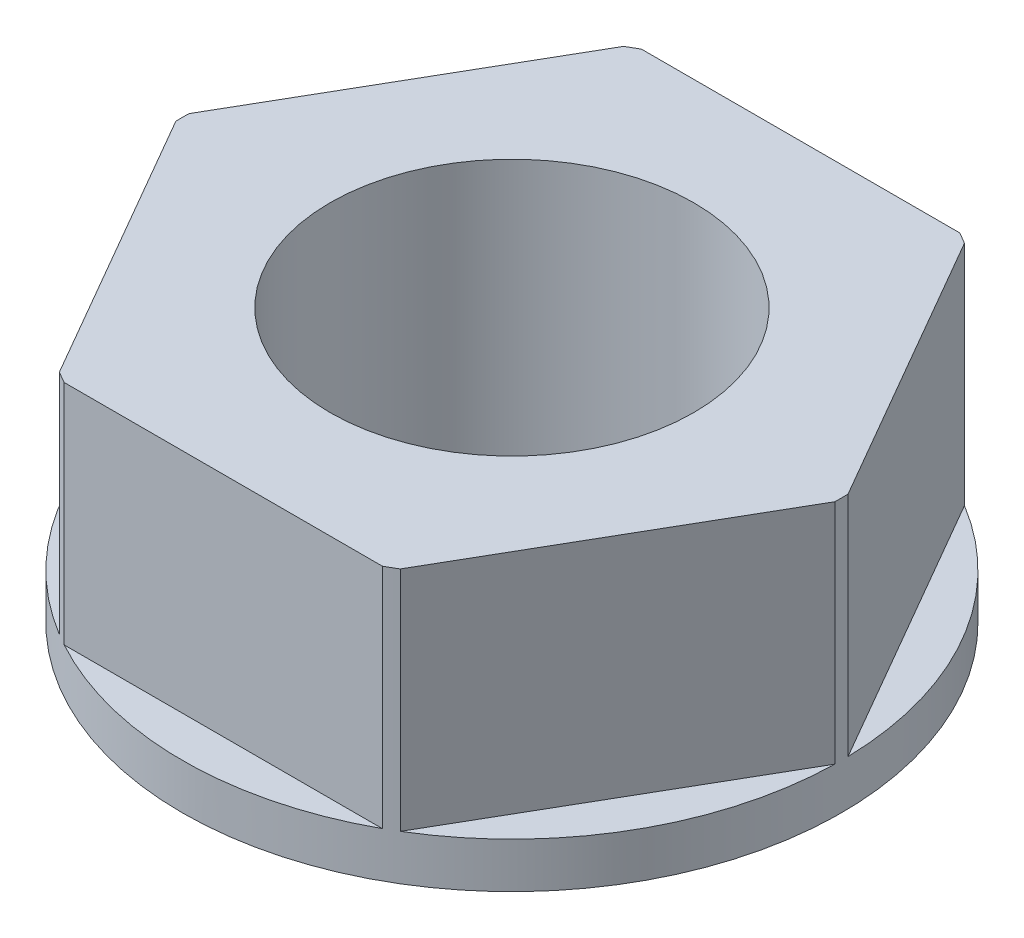
SolidWorks part; units mm, degrees
ref_plane "Front Plane" through (0, 0, 0) normal (0, 0, 1) x (1, 0, 0)
ref_plane "Top Plane" through (0, 0, 0) normal (0, 1, 0) x (1, 0, 0)
ref_plane "Right Plane" through (0, 0, 0) normal (1, 0, 0) x (0, 0, -1)
sketch "Sketch1" plane through (0, 0, 0) normal (0, 1, 0) x (1, 0, 0)
  circle A0 centre (0, 0) radius 7.25
  dimension "D1" = 14.5
extrude "Boss-Extrude1" add sketch "Sketch1" along normal blind 1
sketch "Sketch2" plane through (0, 1, 0) normal (0, 1, 0) x (1, 0, 0)
  line L1 (3.6662, 6.35) -> (-3.6662, 6.35)
  line L2 (-3.6662, 6.35) -> (-7.3323, 0)
  line L3 (-7.3323, 0) -> (-3.6662, -6.35)
  line L4 (-3.6662, -6.35) -> (3.6662, -6.35)
  line L5 (3.6662, -6.35) -> (7.3323, 0)
  line L6 (7.3323, 0) -> (3.6662, 6.35)
  circle A0 centre (0, 0) radius 6.35 construction
  circle A2 centre (0, 0) radius 7.25
  circle A3 centre (0, 0) radius 7.25
  point P1 (0, 0.081)
  circle M8 centre (0, 0) radius 7.25
  dimension "D1" = 12.7
  dimension "D2" = 0
extrude "Boss-Extrude2" add sketch "Sketch2" along normal blind 5 contours L6 L1 L2 L3 L4 L5 M8
sketch "Sketch3" plane through (0, 6, 0) normal (0, 1, 0) x (1, 0, 0)
  circle A0 centre (0, 0) radius 4
  dimension "D1" = 8
extrude "Cut-Extrude1" cut sketch "Sketch3" against normal through all
